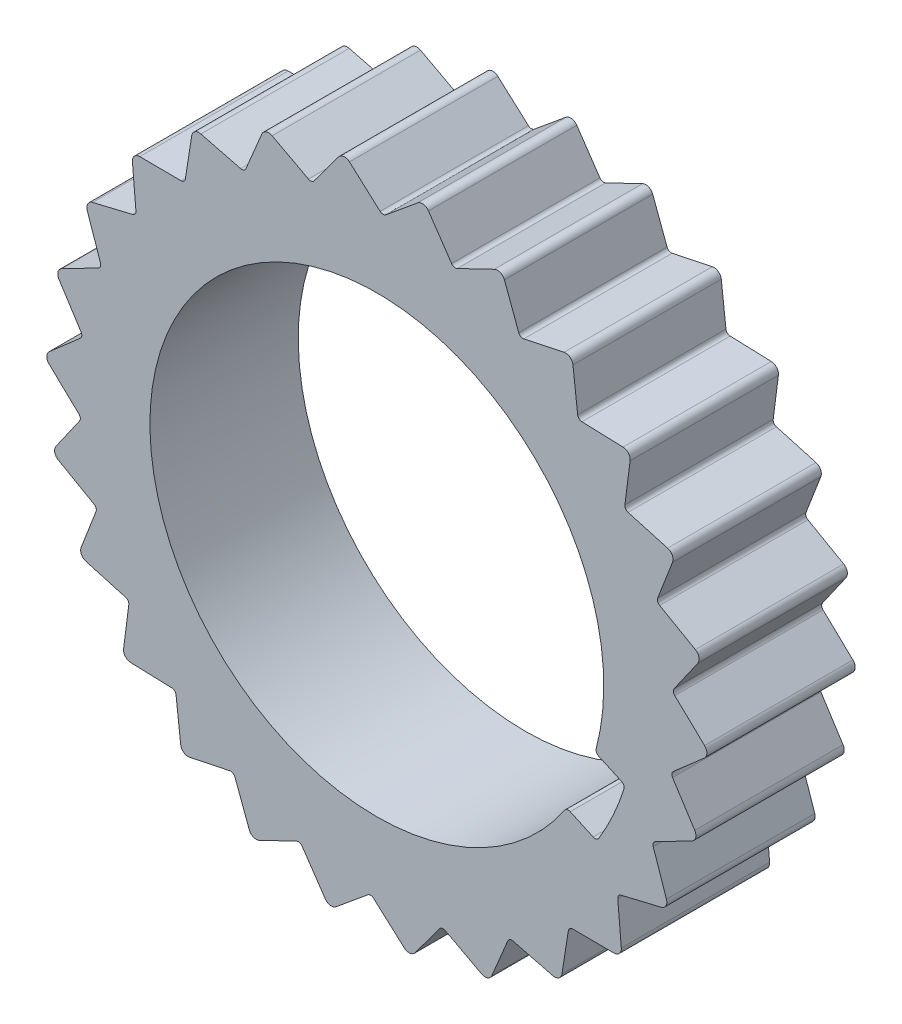
SolidWorks part; units mm, degrees
material "Chêne"
ref_plane "Plan de face" through (0, 0, 0) normal (0, 0, 1) x (1, 0, 0)
ref_plane "Plan de dessus" through (0, 0, 0) normal (0, 1, 0) x (1, 0, 0)
ref_plane "Plan de droite" through (0, 0, 0) normal (1, 0, 0) x (0, 0, -1)
sketch "Esquisse1" plane through (0, 0, 0) normal (0, 0, 1) x (1, 0, 0)
  line L0 (14.953, -4.2772) -> (16.5018, -4.9824)
  line L1 (13.0383, -8.4787) -> (14.587, -9.1845)
  line L29 (19.9364, 9.5309) -> (18.936, 6.9455)
  line L32 (19.0673, 6.5766) -> (21.4759, 5.2041)
  line L33 (21.638, 4.4829) -> (20.0479, 2.212)
  line L34 (20.0871, 1.8224) -> (22.0973, -0.0866)
  line L35 (22.082, -0.8257) -> (19.9947, -2.6501)
  line L36 (19.9395, -3.0377) -> (21.4344, -5.3724)
  line L37 (21.2428, -6.0863) -> (18.7795, -7.3581)
  line L38 (18.6331, -7.7213) -> (19.5259, -10.3458)
  line L39 (19.169, -10.9931) -> (16.4729, -11.6385)
  line L40 (16.2439, -11.9561) -> (16.4826, -14.7181)
  line L41 (15.9811, -15.2611) -> (13.2089, -15.2426)
  line L42 (12.9106, -15.4961) -> (12.4814, -18.2349)
  line L43 (11.8645, -18.6422) -> (9.1773, -17.9608)
  line L44 (8.8269, -18.1355) -> (7.7548, -20.692)
  line L45 (7.0584, -20.9398) -> (4.6124, -19.6351)
  line L46 (4.2303, -19.721) -> (2.5775, -21.9466)
  line L47 (1.842, -22.0205) -> (-0.2207, -20.1684)
  line L48 (-0.6121, -20.1603) -> (-2.7495, -21.9257)
  line L49 (-3.4813, -21.8215) -> (-5.0409, -19.5295)
  line L50 (-5.419, -19.428) -> (-7.9168, -20.6306)
  line L51 (-8.6024, -20.3543) -> (-9.5681, -17.7557)
  line L52 (-9.911, -17.5666) -> (-12.624, -18.1365)
  line L53 (-13.2235, -17.7041) -> (-13.5393, -14.9499)
  line L54 (-13.8269, -14.6843) -> (-16.5975, -14.5884)
  line L55 (-17.0762, -14.0251) -> (-16.7236, -11.2753)
  line L56 (-16.9393, -10.9486) -> (-19.6064, -10.1924)
  line L57 (-19.9364, -9.5309) -> (-18.936, -6.9455)
  line L58 (-19.0673, -6.5766) -> (-21.4759, -5.2041)
  line L59 (-21.638, -4.4829) -> (-20.0479, -2.212)
  line L60 (-20.0871, -1.8224) -> (-22.0973, 0.0866)
  line L61 (-22.082, 0.8257) -> (-19.9947, 2.6501)
  line L62 (-19.9395, 3.0377) -> (-21.4344, 5.3724)
  line L63 (-21.2428, 6.0863) -> (-18.7795, 7.3581)
  line L64 (-18.6331, 7.7213) -> (-19.5259, 10.3458)
  line L65 (-19.169, 10.9931) -> (-16.4729, 11.6385)
  line L66 (-16.2439, 11.9561) -> (-16.4826, 14.7181)
  line L67 (-15.9811, 15.2611) -> (-13.2089, 15.2426)
  line L68 (-12.9106, 15.4961) -> (-12.4814, 18.2349)
  line L69 (-11.8645, 18.6422) -> (-9.1773, 17.9608)
  line L70 (-8.8269, 18.1355) -> (-7.7548, 20.692)
  line L71 (-7.0584, 20.9398) -> (-4.6124, 19.6351)
  line L72 (-4.2303, 19.721) -> (-2.5775, 21.9466)
  line L73 (-1.842, 22.0205) -> (0.2207, 20.1684)
  line L74 (0.6121, 20.1603) -> (2.7495, 21.9257)
  line L75 (3.4813, 21.8215) -> (5.0409, 19.5295)
  line L76 (5.419, 19.428) -> (7.9168, 20.6306)
  line L77 (8.6024, 20.3543) -> (9.5681, 17.7557)
  line L78 (9.911, 17.5666) -> (12.624, 18.1365)
  line L79 (16.9393, 10.9486) -> (19.6064, 10.1924)
  line L80 (13.2235, 17.7041) -> (13.5393, 14.9499)
  line L130 (13.8269, 14.6843) -> (16.5975, 14.5884)
  line L131 (17.0762, 14.0251) -> (16.7236, 11.2753)
  arc A0 (12.6655, -8.5834) -> (14.7874, -3.9272) centre (0, 0) cw
  arc A1 (16.6631, -5.3471) -> (14.968, -9.0669) centre (0, 0) cw
  arc A2 (14.953, -4.2772) -> (14.7874, -3.9272) centre (15.0774, -4.0042) cw
  arc A3 (16.6631, -5.3471) -> (16.5018, -4.9824) centre (16.3774, -5.2555) ccw
  arc A4 (14.587, -9.1845) -> (14.968, -9.0669) centre (14.7114, -8.9115) ccw
  arc A5 (19.9364, 9.5309) -> (19.6064, 10.1924) centre (19.4701, 9.7114) ccw
  arc A6 (19.0673, 6.5766) -> (18.936, 6.9455) centre (19.2158, 6.8372) cw
  arc A7 (16.9393, 10.9486) -> (16.7236, 11.2753) centre (17.0212, 11.2372) cw
  arc A8 (19.0673, 6.5766) -> (18.936, 6.9455) centre (19.2158, 6.8372) cw
  arc A9 (21.638, 4.4829) -> (21.4759, 5.2041) centre (21.2284, 4.7697) ccw
  arc A10 (20.0871, 1.8224) -> (20.0479, 2.212) centre (20.2937, 2.0399) cw
  arc A11 (20.0871, 1.8224) -> (20.0479, 2.212) centre (20.2937, 2.0399) cw
  arc A12 (22.082, -0.8257) -> (22.0973, -0.0866) centre (21.753, -0.4492) ccw
  arc A13 (19.9395, -3.0377) -> (19.9947, -2.6501) centre (20.1922, -2.876) cw
  arc A14 (19.9395, -3.0377) -> (19.9947, -2.6501) centre (20.1922, -2.876) cw
  arc A15 (21.2428, -6.0863) -> (21.4344, -5.3724) centre (21.0134, -5.642) ccw
  arc A16 (18.6331, -7.7213) -> (18.7795, -7.3581) centre (18.9171, -7.6247) cw
  arc A17 (18.6331, -7.7213) -> (18.7795, -7.3581) centre (18.9171, -7.6247) cw
  arc A18 (19.169, -10.9931) -> (19.5259, -10.3458) centre (19.0525, -10.5069) ccw
  arc A19 (16.2439, -11.9561) -> (16.4729, -11.6385) centre (16.5427, -11.9303) cw
  arc A20 (16.2439, -11.9561) -> (16.4729, -11.6385) centre (16.5427, -11.9303) cw
  arc A21 (15.9811, -15.2611) -> (16.4826, -14.7181) centre (15.9845, -14.7611) ccw
  arc A22 (12.9106, -15.4961) -> (13.2089, -15.2426) centre (13.2069, -15.5426) cw
  arc A23 (12.9106, -15.4961) -> (13.2089, -15.2426) centre (13.2069, -15.5426) cw
  arc A24 (11.8645, -18.6422) -> (12.4814, -18.2349) centre (11.9874, -18.1575) ccw
  arc A25 (8.8269, -18.1355) -> (9.1773, -17.9608) centre (9.1036, -18.2515) cw
  arc A26 (8.8269, -18.1355) -> (9.1773, -17.9608) centre (9.1036, -18.2515) cw
  arc A27 (7.0584, -20.9398) -> (7.7548, -20.692) centre (7.2937, -20.4987) ccw
  arc A28 (4.2303, -19.721) -> (4.6124, -19.6351) centre (4.4712, -19.8998) cw
  arc A29 (4.2303, -19.721) -> (4.6124, -19.6351) centre (4.4712, -19.8998) cw
  arc A30 (1.842, -22.0205) -> (2.5775, -21.9466) centre (2.1761, -21.6485) ccw
  arc A31 (-0.6121, -20.1603) -> (-0.2207, -20.1684) centre (-0.4211, -20.3916) cw
  arc A32 (-0.6121, -20.1603) -> (-0.2207, -20.1684) centre (-0.4211, -20.3916) cw
  arc A33 (-3.4813, -21.8215) -> (-2.7495, -21.9257) centre (-3.068, -21.5402) ccw
  arc A34 (-5.419, -19.428) -> (-5.0409, -19.5295) centre (-5.2889, -19.6983) cw
  arc A35 (-5.419, -19.428) -> (-5.0409, -19.5295) centre (-5.2889, -19.6983) cw
  arc A36 (-8.6024, -20.3543) -> (-7.9168, -20.6306) centre (-8.1337, -20.1801) ccw
  arc A37 (-9.911, -17.5666) -> (-9.5681, -17.7557) centre (-9.8493, -17.8602) cw
  arc A38 (-9.911, -17.5666) -> (-9.5681, -17.7557) centre (-9.8493, -17.8602) cw
  arc A39 (-13.2235, -17.7041) -> (-12.624, -18.1365) centre (-12.7268, -17.6472) ccw
  arc A40 (-13.8269, -14.6843) -> (-13.5393, -14.9499) centre (-13.8373, -14.9841) cw
  arc A41 (-13.8269, -14.6843) -> (-13.5393, -14.9499) centre (-13.8373, -14.9841) cw
  arc A42 (-17.0762, -14.0251) -> (-16.5975, -14.5884) centre (-16.5802, -14.0887) ccw
  arc A43 (-16.9393, -10.9486) -> (-16.7236, -11.2753) centre (-17.0212, -11.2372) cw
  arc A44 (-16.9393, -10.9486) -> (-16.7236, -11.2753) centre (-17.0212, -11.2372) cw
  arc A45 (-19.9364, -9.5309) -> (-19.6064, -10.1924) centre (-19.4701, -9.7114) ccw
  arc A46 (-19.0673, -6.5766) -> (-18.936, -6.9455) centre (-19.2158, -6.8372) cw
  arc A47 (-19.0673, -6.5766) -> (-18.936, -6.9455) centre (-19.2158, -6.8372) cw
  arc A48 (-21.638, -4.4829) -> (-21.4759, -5.2041) centre (-21.2284, -4.7697) ccw
  arc A49 (-20.0871, -1.8224) -> (-20.0479, -2.212) centre (-20.2937, -2.0399) cw
  arc A50 (-20.0871, -1.8224) -> (-20.0479, -2.212) centre (-20.2937, -2.0399) cw
  arc A51 (-22.082, 0.8257) -> (-22.0973, 0.0866) centre (-21.753, 0.4492) ccw
  arc A52 (-19.9395, 3.0377) -> (-19.9947, 2.6501) centre (-20.1922, 2.876) cw
  arc A53 (-19.9395, 3.0377) -> (-19.9947, 2.6501) centre (-20.1922, 2.876) cw
  arc A54 (-21.2428, 6.0863) -> (-21.4344, 5.3724) centre (-21.0134, 5.642) ccw
  arc A55 (-18.6331, 7.7213) -> (-18.7795, 7.3581) centre (-18.9171, 7.6247) cw
  arc A56 (-18.6331, 7.7213) -> (-18.7795, 7.3581) centre (-18.9171, 7.6247) cw
  arc A57 (-19.169, 10.9931) -> (-19.5259, 10.3458) centre (-19.0525, 10.5069) ccw
  arc A58 (-16.2439, 11.9561) -> (-16.4729, 11.6385) centre (-16.5427, 11.9303) cw
  arc A59 (-16.2439, 11.9561) -> (-16.4729, 11.6385) centre (-16.5427, 11.9303) cw
  arc A60 (-15.9811, 15.2611) -> (-16.4826, 14.7181) centre (-15.9845, 14.7611) ccw
  arc A61 (-12.9106, 15.4961) -> (-13.2089, 15.2426) centre (-13.2069, 15.5426) cw
  arc A62 (-12.9106, 15.4961) -> (-13.2089, 15.2426) centre (-13.2069, 15.5426) cw
  arc A63 (-11.8645, 18.6422) -> (-12.4814, 18.2349) centre (-11.9874, 18.1575) ccw
  arc A64 (-8.8269, 18.1355) -> (-9.1773, 17.9608) centre (-9.1036, 18.2515) cw
  arc A65 (-8.8269, 18.1355) -> (-9.1773, 17.9608) centre (-9.1036, 18.2515) cw
  arc A66 (-7.0584, 20.9398) -> (-7.7548, 20.692) centre (-7.2937, 20.4987) ccw
  arc A67 (-4.2303, 19.721) -> (-4.6124, 19.6351) centre (-4.4712, 19.8998) cw
  arc A68 (-4.2303, 19.721) -> (-4.6124, 19.6351) centre (-4.4712, 19.8998) cw
  arc A69 (-1.842, 22.0205) -> (-2.5775, 21.9466) centre (-2.1761, 21.6485) ccw
  arc A70 (0.6121, 20.1603) -> (0.2207, 20.1684) centre (0.4211, 20.3916) cw
  arc A71 (0.6121, 20.1603) -> (0.2207, 20.1684) centre (0.4211, 20.3916) cw
  arc A72 (3.4813, 21.8215) -> (2.7495, 21.9257) centre (3.068, 21.5402) ccw
  arc A73 (5.419, 19.428) -> (5.0409, 19.5295) centre (5.2889, 19.6983) cw
  arc A74 (5.419, 19.428) -> (5.0409, 19.5295) centre (5.2889, 19.6983) cw
  arc A75 (8.6024, 20.3543) -> (7.9168, 20.6306) centre (8.1337, 20.1801) ccw
  arc A76 (9.911, 17.5666) -> (9.5681, 17.7557) centre (9.8493, 17.8602) cw
  arc A77 (9.911, 17.5666) -> (9.5681, 17.7557) centre (9.8493, 17.8602) cw
  arc A78 (13.2235, 17.7041) -> (12.624, 18.1365) centre (12.7268, 17.6472) ccw
  arc A79 (13.8269, 14.6843) -> (13.5393, 14.9499) centre (13.8373, 14.9841) cw
  arc A80 (13.8269, 14.6843) -> (13.5393, 14.9499) centre (13.8373, 14.9841) cw
  arc A81 (17.0762, 14.0251) -> (16.5975, 14.5884) centre (16.5802, 14.0887) ccw
  arc A82 (16.9393, 10.9486) -> (16.7236, 11.2753) centre (17.0212, 11.2372) cw
  arc A83 (13.0383, -8.4787) -> (12.6655, -8.5834) centre (12.9139, -8.7517) ccw
  point P36 (18.8428, 6.7045)
  point P51 (18.8428, 6.7045)
  point P116 (0, 0)
  point P374 (0, 0)
extrude "Boss.-Extru.1" add sketch "Esquisse1" along normal blind 10 contours L131 A81 L130 A79 L80 A78 L78 A76 L77 A75 L76 A73 L75 A72 L74 A70 L73 A69 L72 A67 L71 A66 L70 A64 L69 A63 L68 A61 L67 A60 L66 A58 L65 A57 L64 A55 L63 A54 L62 A52 L61 A51 L60 A49 L59 A48 L58 A46 L57 A45 L56
